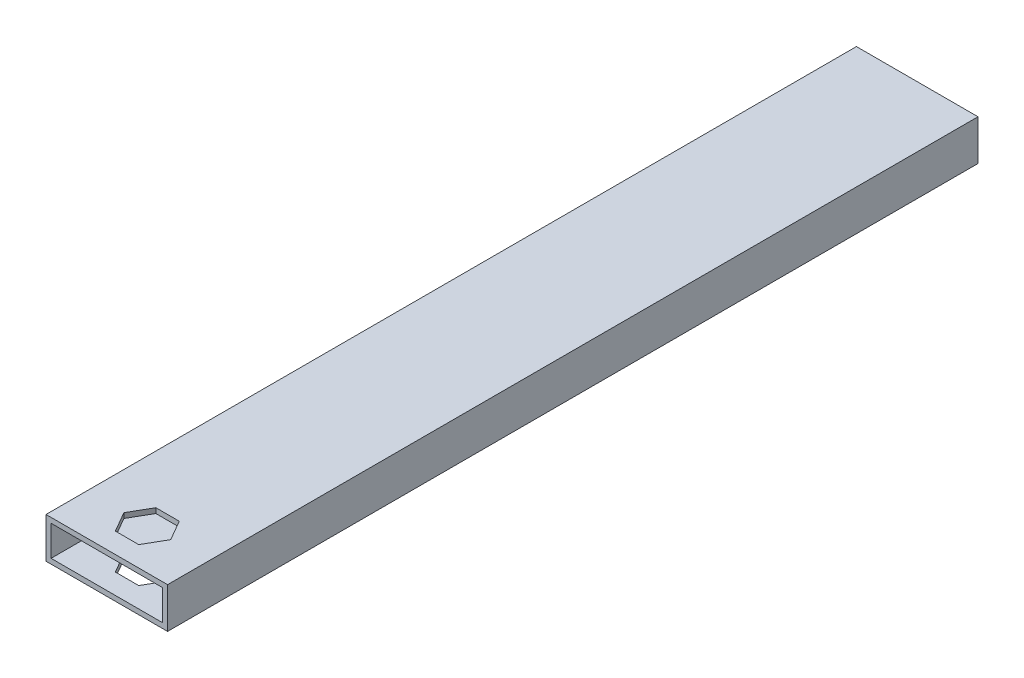
SolidWorks part; units mm, degrees
material "6061 Alloy"
ref_plane "Front Plane" through (0, 0, 0) normal (0, 0, 1) x (1, 0, 0)
ref_plane "Top Plane" through (0, 0, 0) normal (0, 1, 0) x (1, 0, 0)
ref_plane "Right Plane" through (0, 0, 0) normal (1, 0, 0) x (0, 0, -1)
sketch "Sketch1" plane through (0, 0, 0) normal (0, 0, 1) x (1, 0, 0)
  line L1 (0, 0) -> (38.1, 0)
  line L2 (0, 0) -> (0, 12.7)
  line L3 (0, 12.7) -> (38.1, 12.7)
  line L4 (38.1, 0) -> (38.1, 12.7)
  dimension "D1" = 38.1
  dimension "D2" = 12.7
extrude "Boss-Extrude1" add sketch "Sketch1" along normal blind 254
sketch "Sketch2" plane through (0, 0, 254) normal (0, 0, 1) x (1, 0, 0)
  line L4 (36.5125, 1.5875) -> (36.5125, 11.1125)
  line L5 (36.5125, 1.5875) -> (36.5125, 11.1125)
  line L6 (1.5875, 11.1125) -> (1.5875, 1.5875)
  line L7 (1.5875, 11.1125) -> (1.5875, 1.5875)
  line L8 (36.5125, 11.1125) -> (1.5875, 11.1125)
  line L9 (1.5875, 1.5875) -> (36.5125, 1.5875)
  line L10 (36.5125, 11.1125) -> (1.5875, 11.1125)
  line L13 (1.5875, 1.5875) -> (36.5125, 1.5875)
  dimension "D1" = 1.5875
extrude "Cut-Extrude1" cut sketch "Sketch2" against normal through all
sketch "Sketch3" plane through (0, 0, 0) normal (0, -1, 0) x (1, 0, 0)
  line L0 (38.1, 254) -> (38.1, 0) construction
  line L1 (26.3823, 241.3) -> (22.7162, 247.65)
  line L2 (22.7162, 247.65) -> (15.3838, 247.65)
  line L3 (15.3838, 247.65) -> (11.7177, 241.3)
  line L4 (11.7177, 241.3) -> (15.3838, 234.95)
  line L5 (15.3838, 234.95) -> (22.7162, 234.95)
  line L6 (22.7162, 234.95) -> (26.3823, 241.3)
  line L8 (0, 254) -> (38.1, 254) construction
  circle A0 centre (19.05, 241.3) radius 6.35 construction
  dimension "D3" = 12.7
  dimension "D1" = 19.05
  dimension "D2" = 12.7
extrude "Cut-Extrude2" cut sketch "Sketch3" against normal through all
